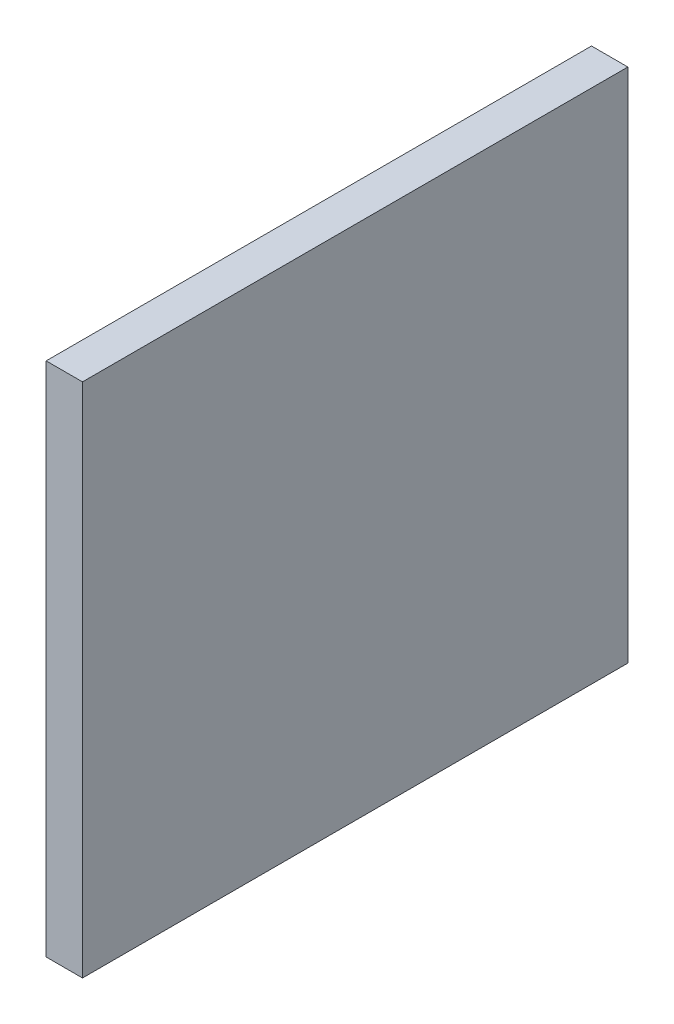
SolidWorks part; units mm, degrees
ref_plane "Alzado" through (0, 0, 0) normal (0, 0, 1) x (1, 0, 0)
ref_plane "Planta" through (0, 0, 0) normal (0, 1, 0) x (1, 0, 0)
ref_plane "Vista lateral" through (0, 0, 0) normal (1, 0, 0) x (0, 0, -1)
sketch "Croquis1" plane through (0, 0, 0) normal (1, 0, 0) x (0, 0, -1)
  line L1 (-90.4593, 49.1741) -> (-15.4593, 49.1741)
  line L2 (-90.4593, 49.1741) -> (-90.4593, -21.8259)
  line L3 (-90.4593, -21.8259) -> (-15.4593, -21.8259)
  line L4 (-15.4593, 49.1741) -> (-15.4593, -21.8259)
  dimension "D1" = 71
  dimension "D2" = 75
extrude "Saliente-Extruir1" add sketch "Croquis1" along normal blind 5
